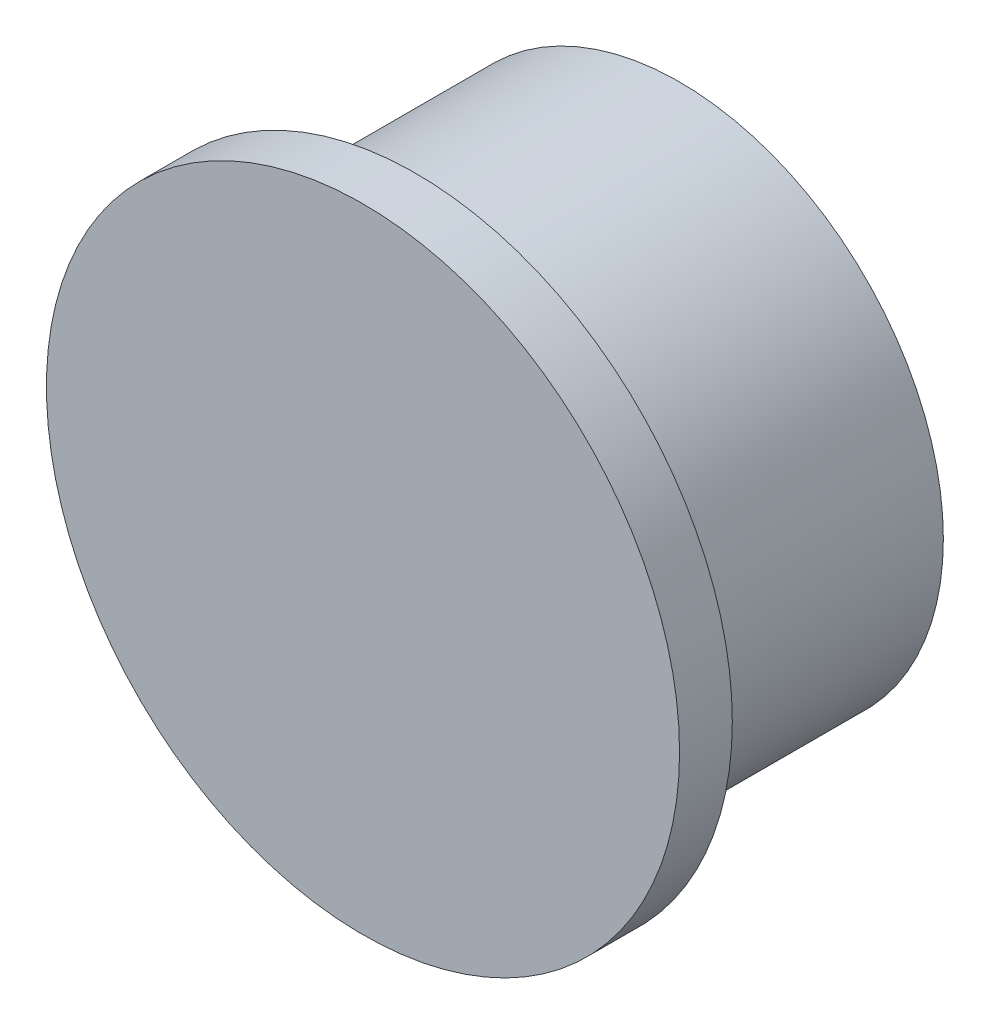
SolidWorks part; units mm, degrees
ref_plane "前视基准面" through (0, 0, 0) normal (0, 0, 1) x (1, 0, 0)
ref_plane "上视基准面" through (0, 0, 0) normal (0, 1, 0) x (1, 0, 0)
ref_plane "右视基准面" through (0, 0, 0) normal (1, 0, 0) x (0, 0, -1)
sketch "草图1" plane through (0, 0, 0) normal (0, 0, 1) x (1, 0, 0)
  circle A0 centre (-41.1616, 8.307) radius 25
  circle A1 centre (-41.1616, 8.307) radius 20
extrude "凸台-拉伸3" add sketch "草图1" along normal blind 25
sketch "草图12" plane through (0, 0, 0) normal (0, 0, -1) x (-1, 0, 0)
  circle A0 centre (41.1616, 8.307) radius 22.5
  circle A1 centre (41.1616, 30.807) radius 1.5
  circle A2 centre (63.6616, 8.307) radius 1.5
  circle A3 centre (41.1616, -14.193) radius 1.5
  circle A4 centre (18.6616, 8.307) radius 1.5
  point P13 (41.1616, 8.307)
  dimension "D1" = 4
extrude "切除-拉伸3" cut sketch "草图12" against normal blind 15 contours A3 | A4 | A1 | A2
sketch "草图13" plane through (0, 0, 25) normal (0, 0, 1) x (1, 0, 0)
  circle A0 centre (-41.1616, 8.307) radius 30
extrude "凸台-拉伸5" add sketch "草图13" along normal blind 5
